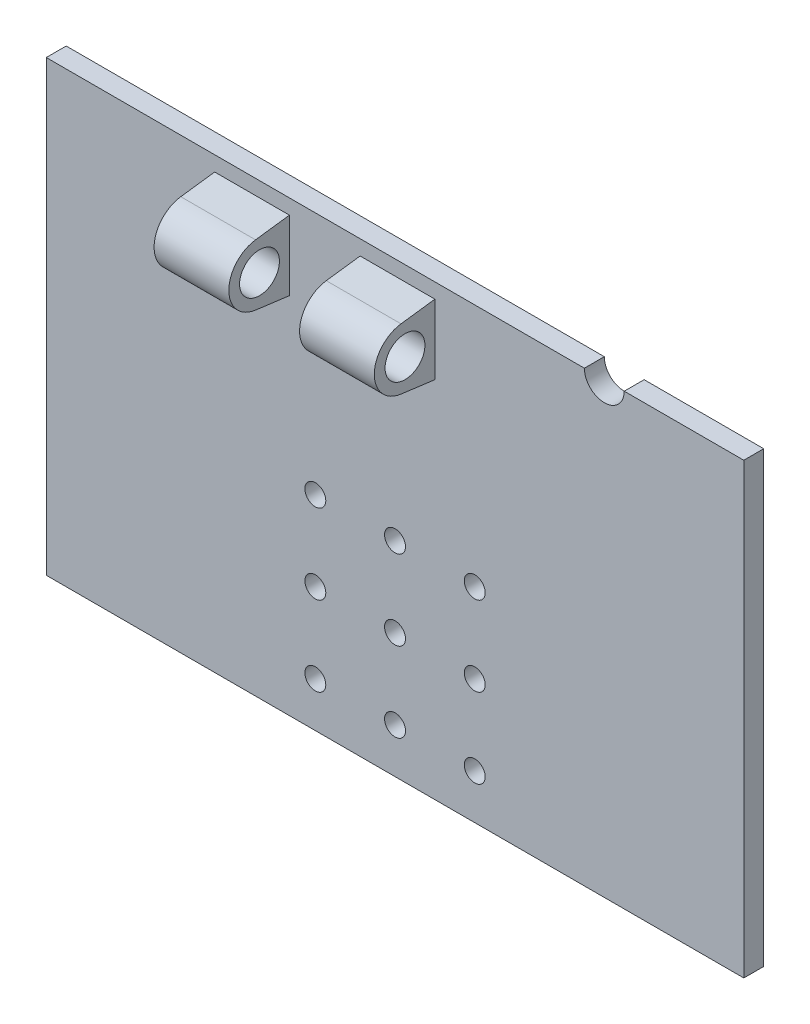
SolidWorks part; units mm, degrees
ref_plane "Front Plane" through (0, 0, 0) normal (0, 0, 1) x (1, 0, 0)
ref_plane "Top Plane" through (0, 0, 0) normal (0, 1, 0) x (1, 0, 0)
ref_plane "Right Plane" through (0, 0, 0) normal (1, 0, 0) x (0, 0, -1)
sketch "Sketch2" plane through (0, 0, 0) normal (0, 0, 1) x (1, 0, 0)
  line L1 (0, 0) -> (70, 0)
  line L2 (0, 0) -> (0, 45)
  line L3 (0, 45) -> (70, 45)
  line L4 (70, 0) -> (70, 45)
  dimension "D1" = 70
  dimension "D2" = 45
extrude "Boss-Extrude1" add sketch "Sketch2" along normal blind 2
sketch "Sketch3" plane through (0, 0, 2) normal (0, 0, 1) x (1, 0, 0)
  line L0 (35, 0) -> (35, 4.5) construction
  line L1 (0, 0) -> (70, 0) construction
  circle A0 centre (35, 4.5) radius 1.05
  circle A1 centre (43, 4.5) radius 1.05
  circle A2 centre (27, 4.5) radius 1.05
  circle A3 centre (27, 12.5) radius 1.05
  circle A4 centre (35, 12.5) radius 1.05
  circle A5 centre (43, 12.5) radius 1.05
  circle A6 centre (27, 20.5) radius 1.05
  circle A7 centre (35, 20.5) radius 1.05
  circle A8 centre (43, 20.5) radius 1.05
  dimension "D2" = 2.1
  dimension "D1" = 4.5
  dimension "D3" = 2
  dimension "D4" = 2
  dimension "D5" = 3
extrude "Cut-Extrude1" cut sketch "Sketch3" against normal blind 2
sketch "Sketch4" plane through (0, 0, 2) normal (0, 0, 1) x (1, 0, 0)
  line L0 (35, 45) -> (35, 40) construction
  line L1 (70, 45) -> (0, 45) construction
  line L2 (35, 40) -> (24.4, 40) construction
  line L3 (24.4, 40) -> (16.9, 40) construction
  line L4 (35, 40) -> (42.5, 40) construction
  circle A0 centre (56, 45) radius 2
  point P7 (35, 40)
  point P9 (27.95, 40)
  point P13 (56, 45)
  dimension "D7" = 4
  dimension "D1" = 5
  dimension "D2" = 7.5
  dimension "D3" = 10.6
  dimension "D4" = 7.5
  dimension "D5" = 3.55
  dimension "D6" = 21
ref_plane "Plane1" through (24.4, 0, 0) normal (-1, 0, 0) x (0, 0, 1)
ref_plane "Plane2" through (27.95, 0, 0) normal (1, 0, 0) x (0, 0, -1)
ref_plane "Plane3" through (16.9, 0, 0) normal (-1, 0, 0) x (0, 0, 1)
sketch "Sketch6" plane through (16.9, 0, 0) normal (-1, 0, 0) x (0, 0, 1)
  line L0 (2, 45) -> (2, 0) construction
  line L1 (2, 45) -> (2, 0) construction
  line L2 (2, 43.5) -> (2, 36.5)
  line L3 (2, 43.5) -> (5.4007, 43.0538)
  line L4 (2, 40) -> (5, 40) construction
  line L5 (2, 36.5) -> (5.4007, 36.9462)
  circle A1 centre (5, 40) radius 2
  arc A3 (5.4007, 36.9462) -> (5.4007, 43.0538) centre (5, 40) ccw
  point P2 (2, 40)
  point P5 (0, 0)
  dimension "D2" = 3
  dimension "D3" = 4
  dimension "D4" = 3.08
  dimension "D1" = 7
extrude "Boss-Extrude2" add sketch "Sketch6" against normal blind 7.5
mirror "Mirror4" about plane through (27.95, 0, 0) normal (1, 0, 0) of "Boss-Extrude2"
extrude "Cut-Extrude2" cut sketch "Sketch4" against normal blind 10 contours A0
